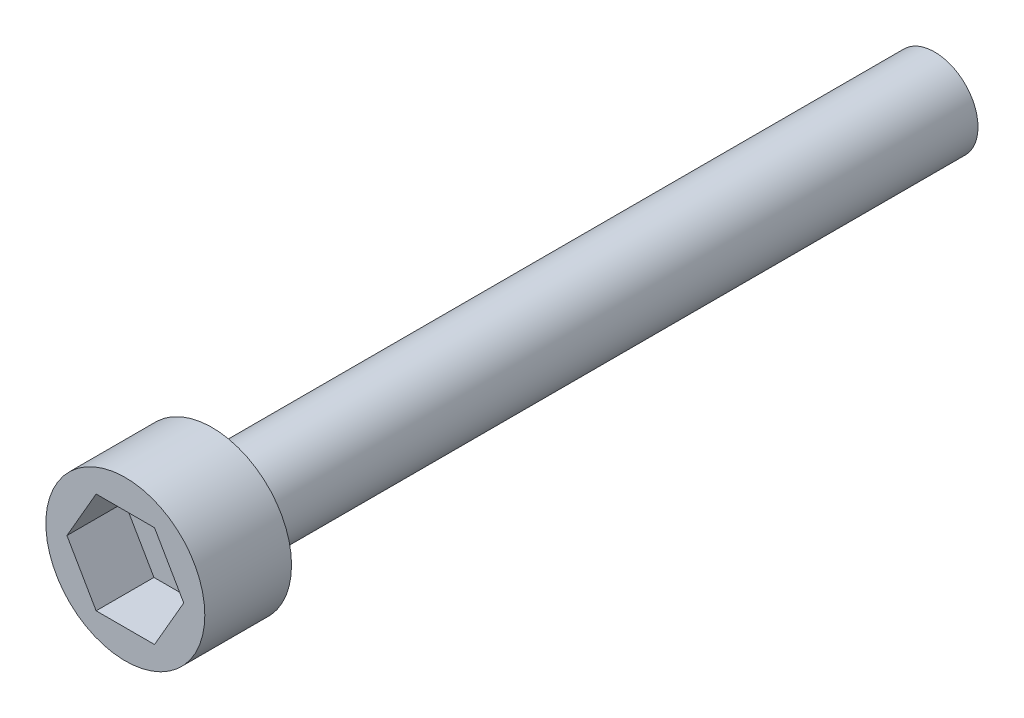
SolidWorks part; units mm, degrees
ref_plane "Plan de face" through (0, 0, 0) normal (0, 0, 1) x (1, 0, 0)
ref_plane "Plan de dessus" through (0, 0, 0) normal (0, 1, 0) x (1, 0, 0)
ref_plane "Plan de droite" through (0, 0, 0) normal (1, 0, 0) x (0, 0, -1)
sketch "Esquisse1" plane through (0, 0, 0) normal (0, 0, 1) x (1, 0, 0)
  circle A0 centre (0, 0) radius 1.5
  dimension "D1" = 3
extrude "Boss.-Extru.1" add sketch "Esquisse1" along normal blind 25
sketch "Esquisse2" plane through (0, 0, 25) normal (0, 0, 1) x (1, 0, 0)
  circle A0 centre (0, 0) radius 2.75
  dimension "D1" = 5.5
extrude "Boss.-Extru.2" add sketch "Esquisse2" along normal blind 3
sketch "Esquisse3" plane through (0, 0, 28) normal (0, 0, 1) x (1, 0, 0)
  line L1 (2.0207, 0) -> (1.0104, 1.75)
  line L2 (1.0104, 1.75) -> (-1.0104, 1.75)
  line L3 (-1.0104, 1.75) -> (-2.0207, 0)
  line L4 (-2.0207, 0) -> (-1.0104, -1.75)
  line L5 (-1.0104, -1.75) -> (1.0104, -1.75)
  line L6 (1.0104, -1.75) -> (2.0207, 0)
  circle A0 centre (0, 0) radius 1.75 construction
  dimension "D1" = 3.5
extrude "Enlèv. mat.-Extru.1" cut sketch "Esquisse3" against normal blind 2
